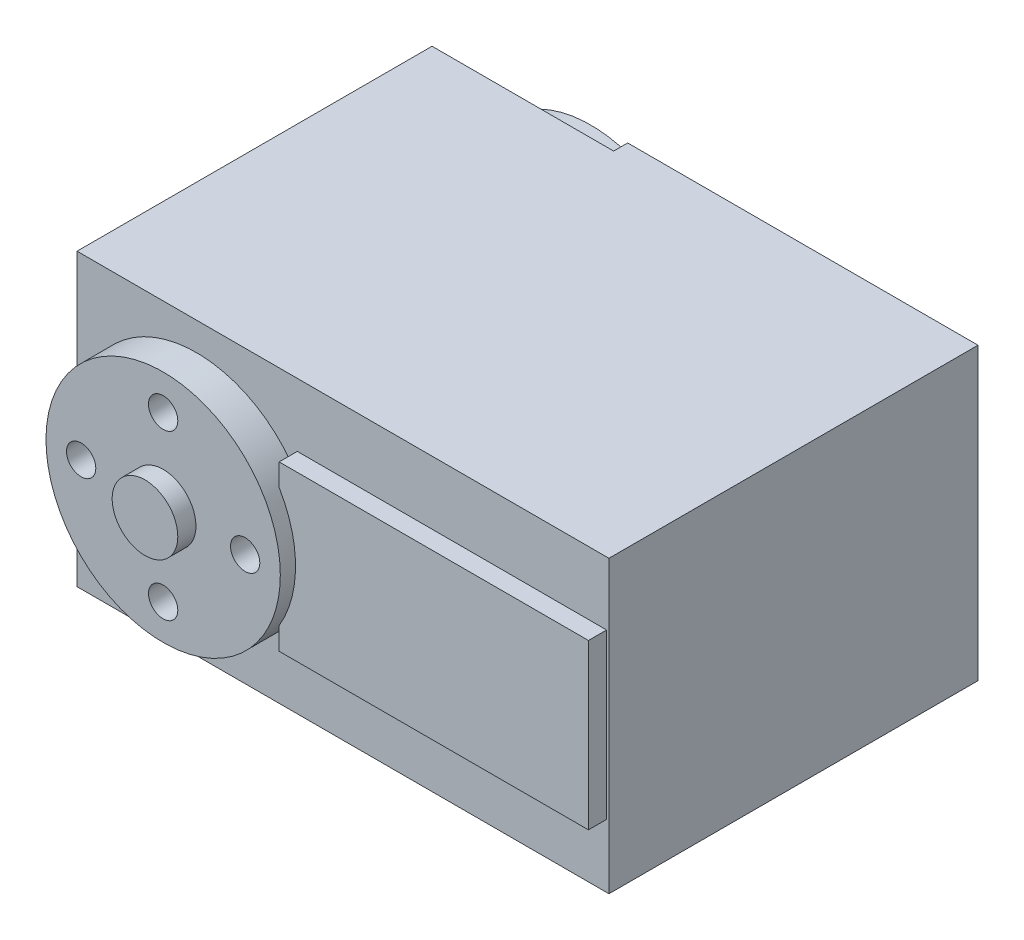
SolidWorks part; units mm, degrees
ref_plane "Front Plane" through (0, 0, 0) normal (0, 0, 1) x (1, 0, 0)
ref_plane "Top Plane" through (0, 0, 0) normal (0, 1, 0) x (1, 0, 0)
ref_plane "Right Plane" through (0, 0, 0) normal (1, 0, 0) x (0, 0, -1)
ref_plane "PZ_m14_400" through (0, 0, -14.4) normal (0, 0, 1) x (1, 0, 0)
sketch "S_box1" plane through (0, 0, -14.4) normal (0, 0, 1) x (1, 0, 0)
  line L0 (-10.2, -12.4) -> (35.2, -12.4)
  line L1 (35.2, -12.4) -> (35.2, 12.4)
  line L2 (35.2, 12.4) -> (-10.2, 12.4)
  line L3 (-10.2, 12.4) -> (-10.2, -12.4)
  dimension "P1" = 10.2
  dimension "P2" = 12.4
  dimension "P3" = 35.2
  dimension "P4" = 12.4
  dimension "P5" = 35.2
  dimension "P6" = 12.4
  dimension "P7" = 10.2
  dimension "P8" = 12.4
extrude "Boss_1" add sketch "S_box1" along normal blind 30.3
ref_plane "PZ_m15_600" through (0, 0, -15.6) normal (0, 0, 1) x (1, 0, 0)
sketch "S_box2" plane through (0, 0, -15.6) normal (0, 0, 1) x (1, 0, 0)
  line L0 (5.3, -12.4) -> (35.2, -12.4)
  line L1 (35.2, -12.4) -> (35.2, 12.4)
  line L2 (35.2, 12.4) -> (5.3, 12.4)
  line L3 (5.3, 12.4) -> (5.3, -12.4)
  dimension "P1" = 5.3
  dimension "P2" = 12.4
  dimension "P3" = 35.2
  dimension "P4" = 12.4
  dimension "P5" = 35.2
  dimension "P6" = 12.4
  dimension "P7" = 5.3
  dimension "P8" = 12.4
extrude "Boss_2" add sketch "S_box2" along normal blind 1.3
ref_plane "PZ_m17_850" through (0, 0, -17.85) normal (0, 0, 1) x (1, 0, 0)
sketch "S_box3" plane through (0, 0, -17.85) normal (0, 0, 1) x (1, 0, 0)
  line L0 (16.7, -9.2) -> (29.9, -9.2)
  line L1 (29.9, -9.2) -> (29.9, 9.2)
  line L2 (29.9, 9.2) -> (16.7, 9.2)
  line L3 (16.7, 9.2) -> (16.7, -9.2)
  dimension "P1" = 16.7
  dimension "P2" = 9.2
  dimension "P3" = 29.9
  dimension "P4" = 9.2
  dimension "P5" = 29.9
  dimension "P6" = 9.2
  dimension "P7" = 16.7
  dimension "P8" = 9.2
extrude "Boss_3" add sketch "S_box3" along normal blind 2.35
ref_plane "PZ_m18_350" through (0, 0, -18.35) normal (0, 0, 1) x (1, 0, 0)
sketch "S_cyl4" plane through (0, 0, -18.35) normal (0, 0, 1) x (1, 0, 0)
  circle A0 centre (0, 0) radius 3
  dimension "D1_S_cyl4" = 6
extrude "Boss_4" add sketch "S_cyl4" along normal blind 4.05
ref_plane "PZ_p15_800" through (0, 0, 15.8) normal (0, 0, 1) x (1, 0, 0)
sketch "S_box5" plane through (0, 0, 15.8) normal (0, 0, 1) x (1, 0, 0)
  line L0 (8.6, -7) -> (35, -7)
  line L1 (35, -7) -> (35, 7)
  line L2 (35, 7) -> (8.6, 7)
  line L3 (8.6, 7) -> (8.6, -7)
  dimension "P1" = 8.6
  dimension "P2" = 7
  dimension "P3" = 35
  dimension "P4" = 7
  dimension "P5" = 35
  dimension "P6" = 7
  dimension "P7" = 8.6
  dimension "P8" = 7
extrude "Boss_5" add sketch "S_box5" along normal blind 1.65
sketch "S_cyl6" plane through (0, 0, 15.8) normal (0, 0, 1) x (1, 0, 0)
  circle A0 centre (0, 0) radius 5.3
  dimension "D1_S_cyl6" = 10.6
extrude "Boss_6" add sketch "S_cyl6" along normal blind 0.6
ref_plane "PZ_m17_750" through (0, 0, -17.75) normal (0, 0, 1) x (1, 0, 0)
sketch "S_cyl7" plane through (0, 0, -17.75) normal (0, 0, 1) x (1, 0, 0)
  circle A0 centre (0, 0) radius 10
  dimension "D1_S_cyl7" = 20
extrude "Boss_7" add sketch "S_cyl7" along normal blind 2.2
sketch "S_cyl8" plane through (0, 0, 15.8) normal (0, 0, 1) x (1, 0, 0)
  circle A0 centre (0, 0) radius 10
  dimension "D1_S_cyl8" = 20
extrude "Boss_8" add sketch "S_cyl8" along normal blind 2.95
ref_plane "PZ_p18_650" through (0, 0, 18.65) normal (0, 0, 1) x (1, 0, 0)
sketch "S_cyl9" plane through (0, 0, 18.65) normal (0, 0, 1) x (1, 0, 0)
  circle A0 centre (0, 0) radius 2.8
  dimension "D1_S_cyl9" = 5.6
extrude "Boss_9" add sketch "S_cyl9" along normal blind 1.65
sketch "S_hole10" plane through (0, 0, -17.85) normal (0, 0, 1) x (1, 0, 0)
  circle A0 centre (7, 0) radius 1.25
  dimension "D1_S_hole10" = 2.5
  dimension "P2" = 7
extrude "Hole_10" cut sketch "S_hole10" along normal blind 2.25
sketch "S_hole11" plane through (0, 0, -17.85) normal (0, 0, 1) x (1, 0, 0)
  circle A0 centre (0, 7) radius 1.25
  dimension "D1_S_hole11" = 2.5
  dimension "P2" = 7
extrude "Hole_11" cut sketch "S_hole11" along normal blind 2.25
sketch "S_hole12" plane through (0, 0, -17.85) normal (0, 0, 1) x (1, 0, 0)
  circle A0 centre (-7, 0) radius 1.25
  dimension "D1_S_hole12" = 2.5
  dimension "P2" = 7
extrude "Hole_12" cut sketch "S_hole12" along normal blind 2.25
sketch "S_hole13" plane through (0, 0, -17.85) normal (0, 0, 1) x (1, 0, 0)
  circle A0 centre (0, -7) radius 1.25
  dimension "D1_S_hole13" = 2.5
  dimension "P2" = 7
extrude "Hole_13" cut sketch "S_hole13" along normal blind 2.25
ref_plane "PZ_p16_250" through (0, 0, 16.25) normal (0, 0, 1) x (1, 0, 0)
sketch "S_hole14" plane through (0, 0, 16.25) normal (0, 0, 1) x (1, 0, 0)
  circle A0 centre (7, 0) radius 1.25
  dimension "D1_S_hole14" = 2.5
  dimension "P2" = 7
extrude "Hole_14" cut sketch "S_hole14" along normal blind 2.6
sketch "S_hole15" plane through (0, 0, 16.25) normal (0, 0, 1) x (1, 0, 0)
  circle A0 centre (0, 7) radius 1.25
  dimension "D1_S_hole15" = 2.5
  dimension "P2" = 7
extrude "Hole_15" cut sketch "S_hole15" along normal blind 2.6
sketch "S_hole16" plane through (0, 0, 16.25) normal (0, 0, 1) x (1, 0, 0)
  circle A0 centre (-7, 0) radius 1.25
  dimension "D1_S_hole16" = 2.5
  dimension "P2" = 7
extrude "Hole_16" cut sketch "S_hole16" along normal blind 2.6
sketch "S_hole17" plane through (0, 0, 16.25) normal (0, 0, 1) x (1, 0, 0)
  circle A0 centre (0, -7) radius 1.25
  dimension "D1_S_hole17" = 2.5
  dimension "P2" = 7
extrude "Hole_17" cut sketch "S_hole17" along normal blind 2.6
ref_plane "PZ_m15_700" through (0, 0, -15.7) normal (0, 0, 1) x (1, 0, 0)
sketch "S_hole18" plane through (0, 0, -15.7) normal (0, 0, 1) x (1, 0, 0)
  circle A0 centre (8.3, -10.25) radius 0.8
  dimension "D1_S_hole18" = 1.6
  dimension "P2" = 8.3
  dimension "P3" = 10.25
extrude "Hole_18" cut sketch "S_hole18" along normal blind 3
sketch "S_hole19" plane through (0, 0, -15.7) normal (0, 0, 1) x (1, 0, 0)
  circle A0 centre (8.3, 10.25) radius 0.8
  dimension "D1_S_hole19" = 1.6
  dimension "P2" = 8.3
  dimension "P3" = 10.25
extrude "Hole_19" cut sketch "S_hole19" along normal blind 3
sketch "S_hole20" plane through (0, 0, -15.7) normal (0, 0, 1) x (1, 0, 0)
  circle A0 centre (32.75, -10.25) radius 0.8
  dimension "D1_S_hole20" = 1.6
  dimension "P2" = 32.75
  dimension "P3" = 10.25
extrude "Hole_20" cut sketch "S_hole20" along normal blind 3
sketch "S_hole21" plane through (0, 0, -15.7) normal (0, 0, 1) x (1, 0, 0)
  circle A0 centre (32.75, 10.25) radius 0.8
  dimension "D1_S_hole21" = 1.6
  dimension "P2" = 32.75
  dimension "P3" = 10.25
extrude "Hole_21" cut sketch "S_hole21" along normal blind 3
equation "\"plate_t\" = 3"
equation "\"clearance\" = 0.5"
